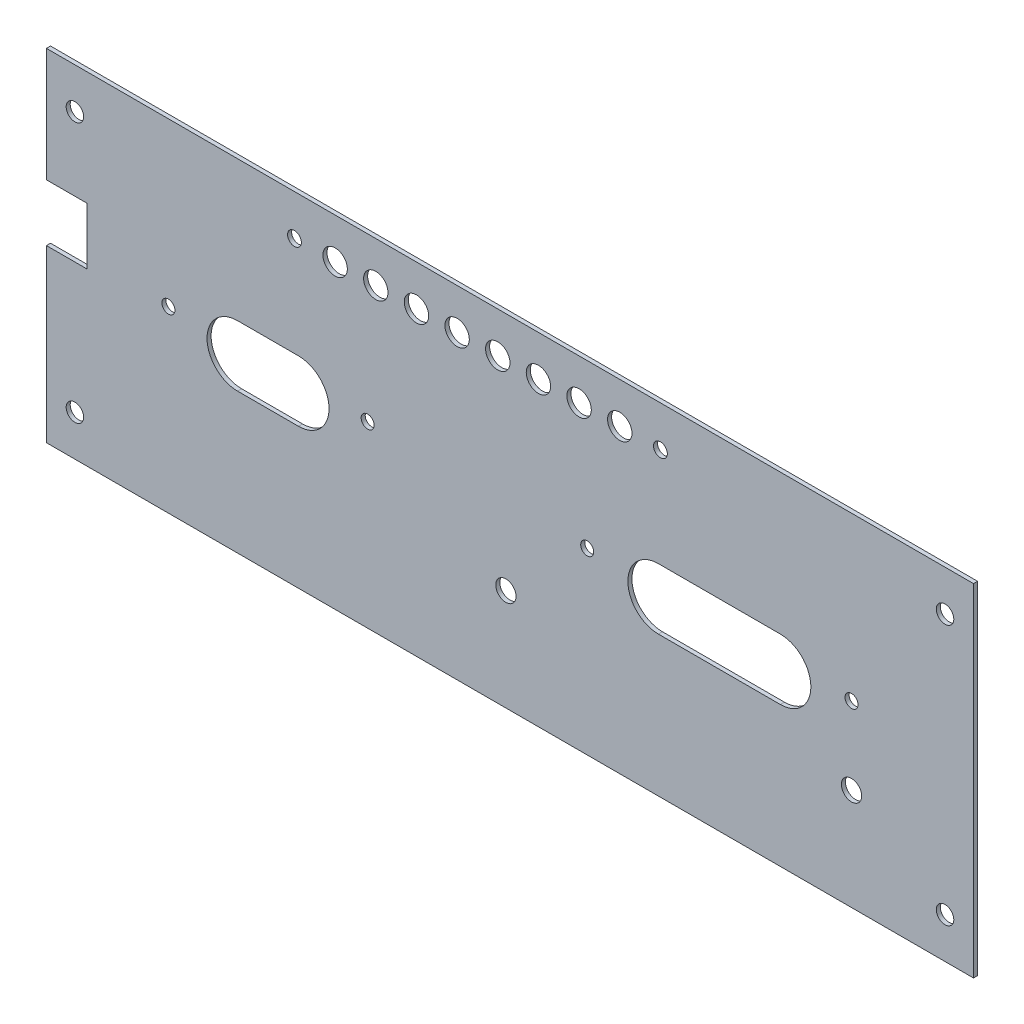
SolidWorks part; units mm, degrees
ref_plane "Спереди" through (0, 0, 0) normal (0, 0, 1) x (1, 0, 0)
ref_plane "Сверху" through (0, 0, 0) normal (0, 1, 0) x (1, 0, 0)
ref_plane "Справа" through (0, 0, 0) normal (1, 0, 0) x (0, 0, -1)
sketch "Эскиз1" plane through (0, 0, 0) normal (0, 0, 1) x (1, 0, 0)
  line L0 (0, 0) -> (58.061, 0) construction
  line L1 (0, 0) -> (0, 47.3035) construction
  line L3 (-114, -42) -> (114, -42)
  line L4 (-114, -42) -> (-114, 42)
  line L5 (-114, 42) -> (114, 42)
  line L6 (114, -42) -> (114, 42)
  circle A8 centre (107, 32) radius 2.15
  circle A9 centre (-107, 32) radius 2.15
  circle A10 centre (-107, -32) radius 2.15
  circle A11 centre (107, -32) radius 2.15
  dimension "D14" = 4.3
  dimension "D15" = 10
  dimension "D16" = 7
  dimension "D1" = 84
  dimension "D2" = 228
extrude "Вытянуть1" add sketch "Эскиз1" along normal blind 1
sketch "Эскиз4" plane through (0, 0, 1) normal (0, 0, 1) x (1, 0, 0)
  line L0 (-114, 42) -> (-114, -42) construction
  line L1 (-114, -42) -> (114, -42) construction
  line L2 (-95.842, 0) -> (24.8302, 0) construction
  line L3 (36.5, 7.5) -> (66.5, 7.5)
  line L4 (36.5, -7.5) -> (66.5, -7.5)
  line L5 (51.5, -2.1564) -> (51.5, -32.5755) construction
  line L6 (-67, 7.5) -> (-52, 7.5)
  line L7 (-67, -7.5) -> (-52, -7.5)
  line L8 (-59.5, -4.8658) -> (-59.5, -32.5755) construction
  line L9 (19, 2) -> (84, 2) construction
  line L10 (0, 76.9526) -> (0, -67.5216) construction
  line L11 (114, -42) -> (114, 42) construction
  line L13 (-118.4641, 0) -> (-104, 0)
  line L14 (-118.4641, 0) -> (-118.4641, 14)
  line L15 (-118.4641, 14) -> (-104, 14)
  line L16 (-104, 0) -> (-104, 14)
  arc A1 (36.5, 7.5) -> (36.5, -7.5) centre (36.5, 0) ccw
  arc A2 (66.5, 7.5) -> (66.5, -7.5) centre (66.5, 0) cw
  circle A3 centre (19, 2) radius 1.6
  circle A4 centre (84, 2) radius 1.6
  arc A5 (-67, 7.5) -> (-67, -7.5) centre (-67, 0) ccw
  arc A6 (-52, 7.5) -> (-52, -7.5) centre (-52, 0) cw
  circle A7 centre (-84, 2) radius 1.6
  circle A8 centre (-35, 2) radius 1.6
  dimension "D3" = 14
  dimension "D6" = 15
  dimension "D5" = 30
  dimension "D8" = 2
  dimension "D4" = 42
  dimension "D9" = 3.2
  dimension "D7" = 32.5
  dimension "D12" = 30
  dimension "D13" = 15
  dimension "D14" = 49
  dimension "D15" = 2
  dimension "D11" = 32.5
  dimension "D10" = 30
  dimension "D2" = 10
  dimension "D16" = 15
  dimension "D17" = 42
extrude "Вырез-Вытянуть2" cut sketch "Эскиз4" against normal blind 1
sketch "Эскиз5" plane through (0, 0, 1) normal (0, 0, 1) x (1, 0, 0)
  line L0 (-8, 40.4363) -> (-8, 19.0193) construction
  line L1 (-53, 32) -> (37, 32) construction
  line L2 (-56.6851, -17) -> (72.361, -17) construction
  line L3 (84, 2) -> (84, -27.7356) construction
  line L4 (-114, -42) -> (114, -42) construction
  line L5 (114, 42) -> (-114, 42) construction
  circle A0 centre (-53, 32) radius 1.7
  circle A1 centre (37, 32) radius 1.7
  circle A4 centre (-13, 32) radius 3
  circle A5 centre (-23, 32) radius 3
  circle A6 centre (-33, 32) radius 3
  circle A7 centre (-43, 32) radius 3
  circle A8 centre (-1, -17) radius 2.5
  circle A9 centre (84, -17) radius 2.5
  circle A10 centre (7, 32) radius 3 [skipped]
  circle A11 centre (-63, 32) radius 3 [skipped]
  circle A12 centre (-3, 32) radius 3 [skipped]
  circle A13 centre (-53, 32) radius 3 [skipped]
  circle A14 centre (-107, 32) radius 2.15 construction
  circle A15 centre (-3, 32) radius 3
  circle A16 centre (7, 32) radius 3
  circle A17 centre (17, 32) radius 3
  circle A18 centre (27, 32) radius 3
  dimension "D1" = 90
  dimension "D2" = 3.4
  dimension "D5" = 30
  dimension "D6" = 6
  dimension "D7" = 85
  dimension "D8" = 5
  dimension "D9" = 54
  dimension "D10" = 10
  dimension "D11" = 10
  dimension "D3" = 74
  dimension "D4" = 25
extrude "Вырез-Вытянуть3" cut sketch "Эскиз5" against normal blind 10
